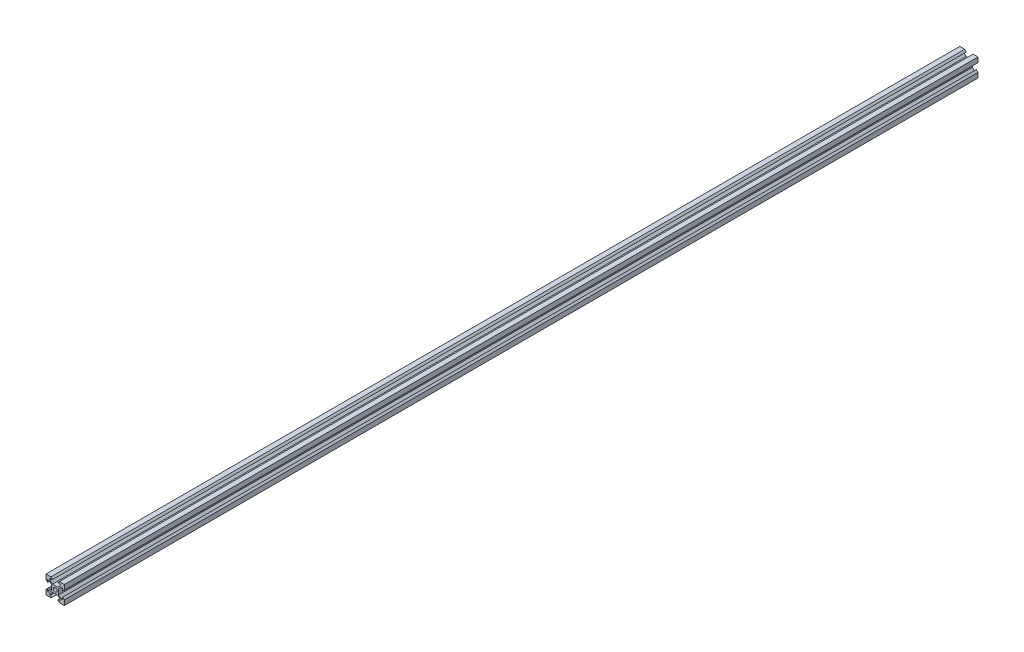
SolidWorks part; units mm, degrees
ref_plane "Front Plane" through (0, 0, 0) normal (0, 0, 1) x (1, 0, 0)
ref_plane "Top Plane" through (0, 0, 0) normal (0, 1, 0) x (1, 0, 0)
ref_plane "Right Plane" through (0, 0, 0) normal (1, 0, 0) x (0, 0, -1)
sketch "Sketch1" plane through (0, 0, 0) normal (0, 0, 1) x (1, 0, 0)
  line L0 (-4.58, 10) -> (-2.885, 8.2)
  line L1 (10, -10) -> (4.58, -10)
  line L2 (10, -10) -> (10, -4.58)
  line L3 (10, 10) -> (4.58, 10)
  line L4 (-10, -10) -> (-10, -4.58)
  line L5 (10, -10) -> (-10, 10) construction
  line L6 (10, 10) -> (-10, -10) construction
  line L7 (-2.8393, 3.9) -> (2.8393, 3.9)
  line L8 (-3.9, 2.8393) -> (-3.9, -2.8393)
  line L9 (-2.8393, -3.9) -> (2.8393, -3.9)
  line L10 (3.9, 2.8393) -> (3.9, -2.8393)
  line L11 (-3.9, 3.9) -> (3.9, -3.9) construction
  line L12 (-3.9, -3.9) -> (3.9, 3.9) construction
  line L13 (4.58, 10) -> (2.885, 8.2)
  line L14 (10, 4.58) -> (10, 10)
  line L15 (-5.5, 8.2) -> (-2.885, 8.2)
  line L16 (-8.2, 5.5) -> (-8.2, 2.885)
  line L17 (-5.5, -8.2) -> (-2.885, -8.2)
  line L18 (8.2, 5.5) -> (8.2, 2.885)
  line L19 (-8.2, 8.2) -> (8.2, -8.2) construction
  line L20 (-8.2, -8.2) -> (8.2, 8.2) construction
  line L21 (10, 4.58) -> (8.2, 2.885)
  line L22 (10, -4.58) -> (8.2, -2.885)
  line L23 (4.58, -10) -> (2.885, -8.2)
  line L24 (-4.58, -10) -> (-2.885, -8.2)
  line L25 (-10, -4.58) -> (-8.2, -2.885)
  line L26 (-10, 4.58) -> (-8.2, 2.885)
  line L27 (0, 14.7958) -> (0, -12.2524) construction
  line L28 (-5.5, 8.2) -> (-5.5, 6.5607)
  line L29 (5.5, 8.2) -> (5.5, 6.5607)
  line L30 (-5.5, 6.5607) -> (-2.8393, 3.9)
  line L31 (2.8393, 3.9) -> (5.5, 6.5607)
  line L32 (-4.58, 10) -> (-10, 10)
  line L33 (2.885, 8.2) -> (5.5, 8.2)
  line L34 (8.2, -2.885) -> (8.2, -5.5)
  line L35 (2.885, -8.2) -> (5.5, -8.2)
  line L36 (-4.58, -10) -> (-10, -10)
  line L37 (-8.2, -2.885) -> (-8.2, -5.5)
  line L38 (-10, 4.58) -> (-10, 10)
  line L39 (8.2, 5.5) -> (6.5607, 5.5)
  line L40 (6.5607, 5.5) -> (3.9, 2.8393)
  line L41 (3.9, -2.8393) -> (6.5607, -5.5)
  line L42 (8.2, -5.5) -> (6.5607, -5.5)
  line L43 (5.5, -8.2) -> (5.5, -6.5607)
  line L44 (5.5, -6.5607) -> (2.8393, -3.9)
  line L45 (-2.8393, -3.9) -> (-5.5, -6.5607)
  line L46 (-5.5, -8.2) -> (-5.5, -6.5607)
  line L47 (-8.2, -5.5) -> (-6.5607, -5.5)
  line L48 (-6.5607, -5.5) -> (-3.9, -2.8393)
  line L49 (-3.9, 2.8393) -> (-6.5607, 5.5)
  line L50 (-8.2, 5.5) -> (-6.5607, 5.5)
  circle A0 centre (0, 0) radius 2.1
  point P0 (0, 0)
  point P35 (0, 0)
  point P62 (0, 0)
  dimension "D3" = 4.2
  dimension "D1" = 20
  dimension "D4" = 9.16
  dimension "D5" = 9.16
  dimension "D6" = 1.8
  dimension "D7" = 6.1
  dimension "D8" = 5.77
  dimension "D10" = 5.5
  dimension "D11" = 5.5
  dimension "D12" = 1.5
  dimension "D13" = 1.5
  dimension "D14" = 5.77
  dimension "D15" = 20
  dimension "D9" = 4
extrude "Boss-Extrude1" add sketch "Sketch1" along normal blind 1000
